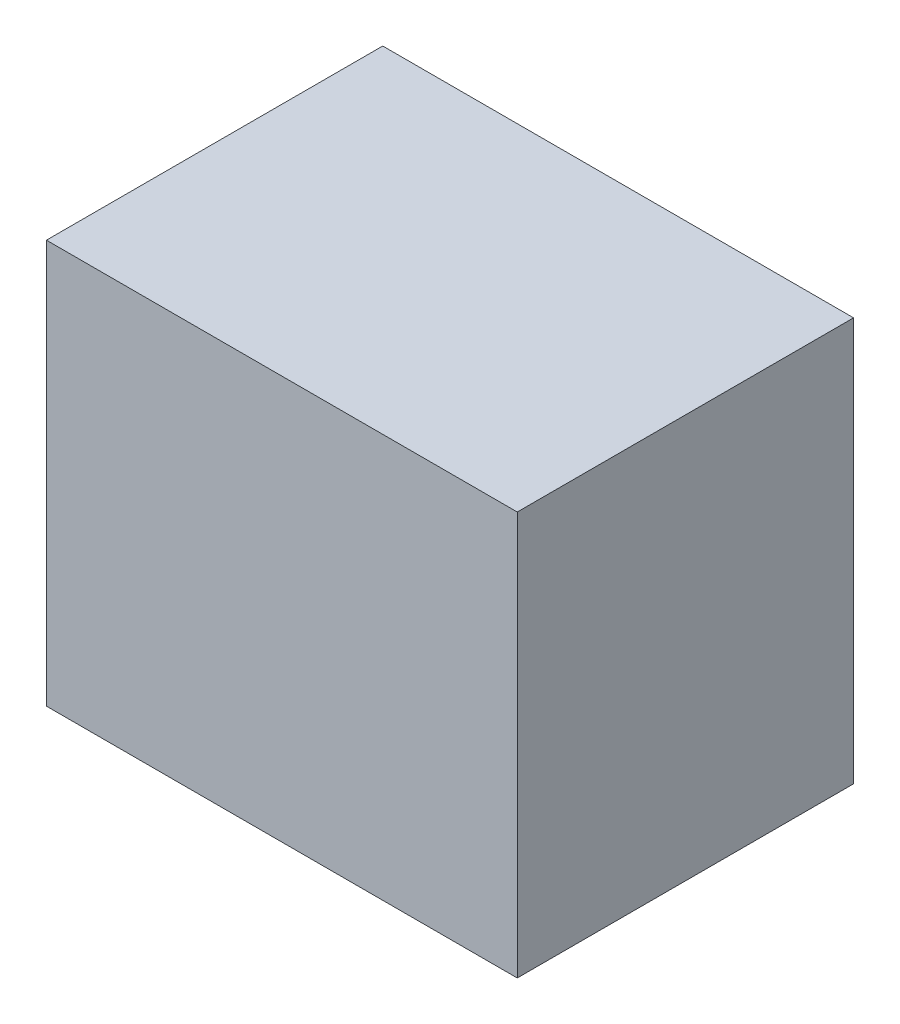
SolidWorks part; units mm, degrees
ref_plane "前视基准面" through (0, 0, 0) normal (0, 0, 1) x (1, 0, 0)
ref_plane "上视基准面" through (0, 0, 0) normal (0, 1, 0) x (1, 0, 0)
ref_plane "右视基准面" through (0, 0, 0) normal (1, 0, 0) x (0, 0, -1)
other "Configuration Table"
sketch "草图1" plane through (0, 0, 0) normal (0, 0, 1) x (1, 0, 0)
  line L1 (-35, -30) -> (35, -30)
  line L2 (-35, -30) -> (-35, 30)
  line L3 (-35, 30) -> (35, 30)
  line L4 (35, -30) -> (35, 30)
  line L5 (-35, -30) -> (35, 30) construction
  line L6 (-35, 30) -> (35, -30) construction
  point P0 (0, 0)
extrude "凸台-拉伸1" add sketch "草图1" along normal blind 50
